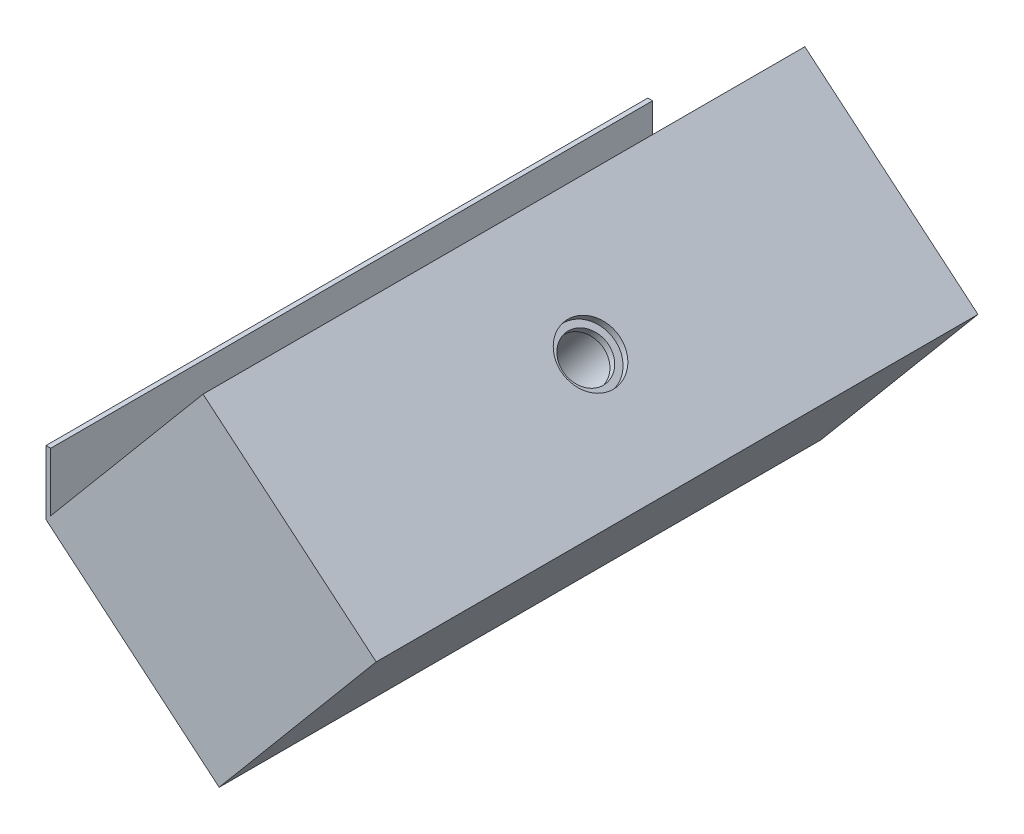
SolidWorks part; units mm, degrees
ref_plane "Front Plane" through (0, 0, 0) normal (0, 0, 1) x (1, 0, 0)
ref_plane "Top Plane" through (0, 0, 0) normal (0, 1, 0) x (1, 0, 0)
ref_plane "Right Plane" through (0, 0, 0) normal (1, 0, 0) x (0, 0, -1)
sketch "Sketch1" plane through (0, 0, 0) normal (0, 0, 1) x (1, 0, 0)
  line L5 (0, 0) -> (0, 86.6681)
  line L6 (0, 86.6681) -> (6.3935, 86.6681)
  line L7 (6.3935, 86.6681) -> (6.3935, 7.6195)
  line L8 (6.3935, 7.6195) -> (199.2642, 237.4738)
  line L9 (199.2642, 237.4738) -> (433.1222, 41.2436)
  line L10 (433.1222, 41.2436) -> (233.858, -196.2302)
  line L11 (0, 0) -> (233.858, -196.2302)
extrude "Boss-Extrude1" add sketch "Sketch1" along normal blind 262.8
sketch "Sketch6" plane through (0, 0, 0) normal (-0.6428, -0.766, 0) x (-0.766, 0.6428, 0)
  line L2 (-305.28, -262.8) -> (0, -262.8) construction
  line L3 (0, -262.8) -> (-305.28, 0) construction
  line L4 (-305.28, 0) -> (0, 0) construction
  line L5 (0, 0) -> (-305.28, -262.8) construction
  circle A0 centre (-152.64, -131.4) radius 36
extrude "Cut-Extrude3" cut sketch "Sketch6" against normal through all both and the other way through all
sketch "Sketch7" plane through (0, 0, 262.8) normal (0, 0, 1) x (1, 0, 0)
  line L0 (233.858, -196.2302) -> (0, 0)
  line L1 (0, 0) -> (0, 86.6681)
  line L2 (0, 86.6681) -> (6.3935, 86.6681)
  line L3 (6.3935, 86.6681) -> (6.3935, 7.6195)
  line L4 (6.3935, 7.6195) -> (199.2642, 237.4738)
  line L5 (199.2642, 237.4738) -> (433.1222, 41.2436)
  line L6 (433.1222, 41.2436) -> (233.858, -196.2302)
extrude "Boss-Extrude4" add sketch "Sketch7" along normal blind 275
sketch "Sketch8" plane through (0, 0, 0) normal (0, 0, -1) x (-1, 0, 0)
  line L0 (0, 0) -> (0, 86.6681)
  line L1 (0, 86.6681) -> (-6.3935, 86.6681)
  line L2 (-6.3935, 86.6681) -> (-6.3935, 7.6195)
  line L3 (-6.3935, 7.6195) -> (-199.2642, 237.4738)
  line L4 (-199.2642, 237.4738) -> (-433.1222, 41.2436)
  line L5 (-433.1222, 41.2436) -> (-233.858, -196.2302)
  line L6 (-233.858, -196.2302) -> (0, 0)
extrude "Boss-Extrude5" add sketch "Sketch8" along normal blind 275
sketch "Sketch11" plane through (199.2642, 237.4738, 0) normal (0.6428, 0.766, 0) x (0.766, -0.6428, 0)
  line L0 (0, -537.8) -> (0, 275)
  line L1 (0, 275) -> (305.28, 275)
  line L2 (305.28, 275) -> (305.28, -537.8)
  line L3 (305.28, -537.8) -> (0, -537.8)
  circle A0 centre (152.64, -131.4) radius 31
extrude "Boss-Extrude6" add sketch "Sketch11" along normal blind 10
sketch "Sketch12" plane through (205.692, 245.1342, 0) normal (0.6428, 0.766, 0) x (0.766, -0.6428, 0)
  line L0 (0, -537.8) -> (0, 275)
  line L1 (0, 275) -> (305.28, 275)
  line L2 (305.28, 275) -> (305.28, -537.8)
  line L3 (305.28, -537.8) -> (0, -537.8)
  circle A0 centre (152.64, -131.4) radius 40
extrude "Boss-Extrude7" add sketch "Sketch12" along normal blind 10
sketch "Sketch13" plane through (0, 0, 0) normal (-0.6428, -0.766, 0) x (-0.766, 0.6428, 0)
  line L0 (-152.5537, -131.1133) -> (0, -131.4) construction
  line L1 (0, -537.8) -> (0, 275) construction
  line L2 (0, -131.4) -> (-57.5999, -131.2917)
  line L3 (-152.5537, -131.1133) -> (-152.5537, -344.7946) construction
  circle A0 centre (-152.5537, -131.1133) radius 36.2994
  circle A1 centre (-57.5999, -131.2917) radius 20.52
  circle A2 centre (-247.5075, -131.2917) radius 20.52
extrude "Cut-Extrude4" cut sketch "Sketch13" against normal blind 170
